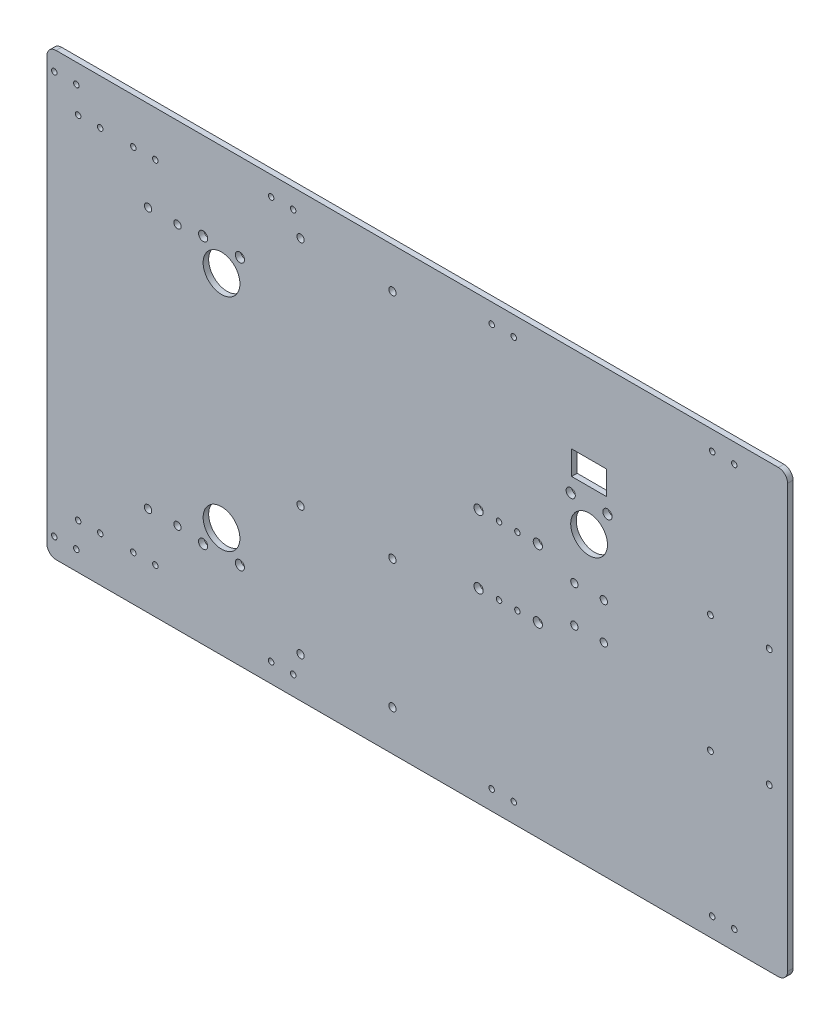
SolidWorks part; units mm, degrees
ref_plane "前视基准面" through (0, 0, 0) normal (0, 0, 1) x (1, 0, 0)
ref_plane "上视基准面" through (0, 0, 0) normal (0, 1, 0) x (1, 0, 0)
ref_plane "右视基准面" through (0, 0, 0) normal (1, 0, 0) x (0, 0, -1)
sketch "Model" plane through (0, 0, 0) normal (0, 0, 1) x (1, 0, 0)
  line L0 (5, 120) -> (398, 120)
  line L3 (5, -120) -> (398, -120)
  line L5 (0, 115) -> (0, -115)
  line L7 (285.5, 72.5) -> (304.5, 72.5)
  line L8 (304.5, 72.5) -> (304.5, 59.5)
  line L9 (304.5, 59.5) -> (285.5, 59.5)
  line L10 (285.5, 59.5) -> (285.5, 72.5)
  line L11 (403, 115) -> (403, -115)
  arc A0 (398, -120) -> (403, -115) centre (398, -115) ccw
  arc A1 (0, -115) -> (5, -120) centre (5, -115) ccw
  circle A2 centre (17, 95.5) radius 1.5
  circle A3 centre (29, 95.5) radius 1.5
  circle A4 centre (47, 95.5) radius 1.5
  circle A5 centre (59, 95.5) radius 1.5
  circle A6 centre (17, -95.5) radius 1.5
  circle A7 centre (29, -95.5) radius 1.5
  circle A8 centre (47, -95.5) radius 1.5
  circle A9 centre (59, -95.5) radius 1.5
  arc A10 (5, 120) -> (0, 115) centre (5, 115) ccw
  circle A11 centre (4, 109.5) radius 1.5
  circle A12 centre (16, 109.5) radius 1.5
  circle A13 centre (4, -109.5) radius 1.5
  circle A14 centre (16, -109.5) radius 1.5
  circle A15 centre (362, 109.5) radius 1.5
  circle A16 centre (374, 109.5) radius 1.5
  circle A17 centre (362, -109.5) radius 1.5
  circle A18 centre (374, -109.5) radius 1.5
  circle A19 centre (361, 32) radius 1.6
  circle A20 centre (393, 32) radius 1.6
  circle A21 centre (393, -32) radius 1.6
  circle A22 centre (361, -32) radius 1.6
  circle A23 centre (188, 98) radius 2
  circle A24 centre (138, 98) radius 2
  circle A25 centre (254, 109.5) radius 1.5
  circle A26 centre (242, 109.5) radius 1.5
  circle A27 centre (188, -98) radius 2
  circle A28 centre (138, -98) radius 2
  circle A29 centre (138, -28) radius 2
  circle A30 centre (188, -28) radius 2
  circle A31 centre (295, 37) radius 10
  circle A32 centre (285, 51.5) radius 2.5
  circle A33 centre (305, 51.5) radius 2.5
  circle A34 centre (256, 18.5) radius 1.5
  circle A35 centre (246, 18.5) radius 1.5
  circle A36 centre (256, -18.5) radius 1.5
  circle A37 centre (246, -18.5) radius 1.5
  circle A38 centre (95, 60) radius 10
  circle A39 centre (105, 72.5) radius 2.5
  circle A40 centre (85, 72.5) radius 2.5
  circle A41 centre (95, -60) radius 10
  circle A42 centre (105, -72.5) radius 2.5
  circle A43 centre (85, -72.5) radius 2.5
  circle A44 centre (134, 109.5) radius 1.5
  circle A45 centre (122, 109.5) radius 1.5
  circle A46 centre (287, 10) radius 2
  circle A47 centre (303, 10) radius 2
  circle A48 centre (303, -10) radius 2
  circle A49 centre (287, -10) radius 2
  circle A50 centre (55.0305, 71.0005) radius 2
  circle A51 centre (71.0305, 71.0005) radius 2
  circle A52 centre (55.0305, -71.0005) radius 2
  circle A53 centre (71.0305, -71.0005) radius 2
  circle A54 centre (254, -109.5) radius 1.5
  circle A55 centre (242, -109.5) radius 1.5
  circle A56 centre (134, -109.5) radius 1.5
  circle A57 centre (122, -109.5) radius 1.5
  circle A58 centre (267.1069, 18.5) radius 2.5
  circle A59 centre (234.8931, 18.5) radius 2.5
  circle A60 centre (267.1069, -18.5) radius 2.5
  circle A61 centre (234.8931, -18.5) radius 2.5
  arc A62 (403, 115) -> (398, 120) centre (398, 115) ccw
  dimension "D1" = 403
extrude "凸台-拉伸1" add sketch "Model" along normal blind 3 contours L11 A62 L0 A10 L5 A1 L3 A0 L9 L10 L7 L8 A2 A3 A4 A5 A6 A7 A8 A9 A11 A12 A13 A14 A15 A16 A17 A18 A19 A20 A21
